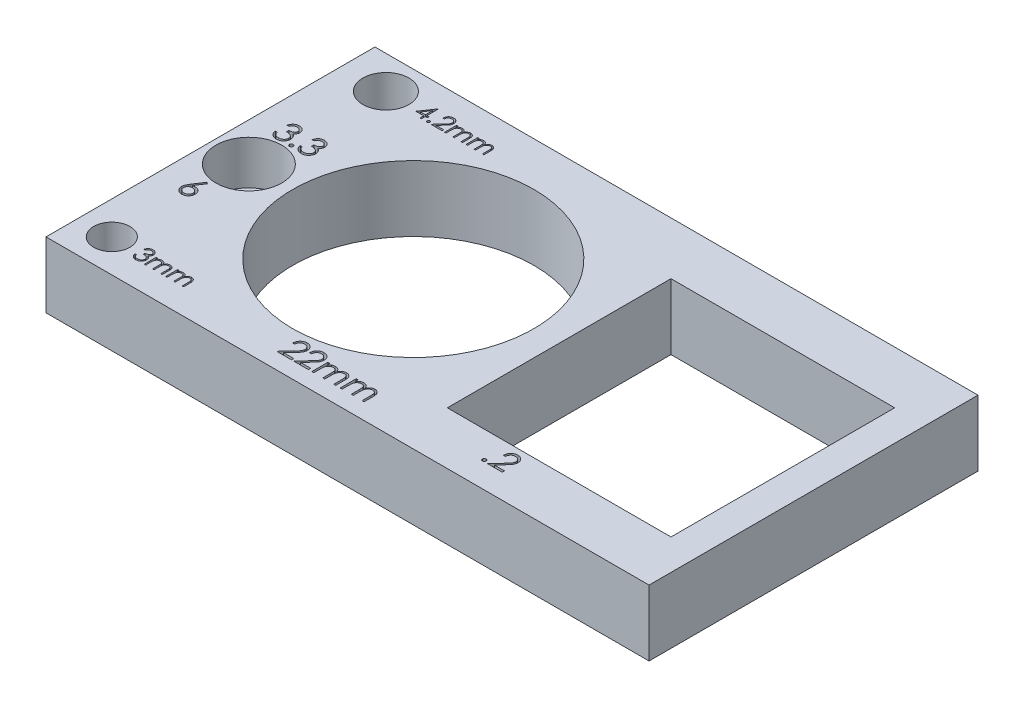
SolidWorks part; units mm, degrees
ref_plane "Front Plane" through (0, 0, 0) normal (0, 0, 1) x (1, 0, 0)
ref_plane "Top Plane" through (0, 0, 0) normal (0, 1, 0) x (1, 0, 0)
ref_plane "Right Plane" through (0, 0, 0) normal (1, 0, 0) x (0, 0, -1)
sketch "Sketch1" plane through (0, 0, 0) normal (0, 1, 0) x (1, 0, 0)
  line L1 (-27.5, -15) -> (27.5, -15)
  line L2 (-27.5, -15) -> (-27.5, 15)
  line L3 (-27.5, 15) -> (27.5, 15)
  line L4 (27.5, -15) -> (27.5, 15)
  line L5 (-27.5, -15) -> (27.5, 15) construction
  line L6 (-27.5, 15) -> (27.5, -15) construction
  point P0 (0, 0)
  dimension "D1" = 55
  dimension "D2" = 30
extrude "Boss-Extrude1" add sketch "Sketch1" along normal blind 6
sketch "Sketch2" plane through (0, 0, 0) normal (0, 1, 0) x (1, 0, 0)
  line L10 (27.5, -15) -> (27.5, 15) construction
  line L11 (24.5, -10) -> (4.5, -10) construction
  line L12 (24.5, -10) -> (24.5, 10) construction
  line L13 (24.5, 10) -> (4.5, 10) construction
  line L14 (4.5, -10) -> (4.5, 10) construction
  line L16 (-27.5, -15) -> (27.5, -15) construction
  line L17 (4.3, -10.2) -> (4.3, 10.2)
  line L18 (24.7, 10.2) -> (4.3, 10.2)
  line L19 (24.7, -10.2) -> (24.7, 10.2)
  line L20 (24.7, -10.2) -> (4.3, -10.2)
  dimension "D1" = 20
  dimension "D2" = 20
  dimension "D3" = 3
  dimension "D4" = 5
  dimension "D5" = 0.2
extrude "Cut-Extrude2" cut sketch "Sketch2" against normal through all and the other way through all
sketch "Sketch4" plane through (0, 0, 0) normal (0, 1, 0) x (1, 0, 0)
  line L0 (27.5, 12) -> (-27.5, 12) construction
  line L1 (27.5, -15) -> (27.5, 15) construction
  line L2 (-27.5, 15) -> (-27.5, -15) construction
  line L3 (27.5, 15) -> (-27.5, 15) construction
  circle A0 centre (-23.5, 12) radius 2.1
  dimension "D2" = 4.2
  dimension "D1" = 3
  dimension "D3" = 4
extrude "Cut-Extrude3" cut sketch "Sketch4" along normal blind 10
sketch "Sketch5" plane through (0, 6, 0) normal (0, 1, 0) x (1, 0, 0)
  line L0 (-27.5, -15) -> (27.5, -15) construction
  line L1 (-27.5, 15) -> (-27.5, -15) construction
  circle A0 centre (-24.5, -12) radius 1.65
  dimension "D1" = 3.3
  dimension "D2" = 3
  dimension "D3" = 3
extrude "Cut-Extrude4" cut sketch "Sketch5" against normal through all
sketch "Sketch6" plane through (0, 6, 0) normal (0, 1, 0) x (1, 0, 0)
  text T0 "4.2mm" font "Century Gothic" height 1.5
extrude "Cut-Extrude5" cut sketch "Sketch6" against normal blind 1
sketch "Sketch7" plane through (0, 6, 0) normal (0, 1, 0) x (1, 0, 0)
  text T0 "3mm" font "Century Gothic" height 1.5
extrude "Cut-Extrude6" cut sketch "Sketch7" against normal blind 1
sketch "Sketch8" plane through (0, 6, 0) normal (0, 1, 0) x (1, 0, 0)
  line L0 (-27.5, 15) -> (-27.5, -15) construction
  circle A0 centre (-24, 0) radius 1.65
  dimension "D1" = 3.3
  dimension "D2" = 3.5
extrude "Cut-Extrude7" cut sketch "Sketch8" against normal through all
sketch "Sketch9" plane through (0, 6, 0) normal (0, 1, 0) x (1, 0, 0)
  circle A0 centre (-24, 0) radius 3
  dimension "D1" = 6
extrude "Cut-Extrude8" cut sketch "Sketch9" against normal blind 4
sketch "Sketch10" plane through (0, 6, 0) normal (0, 1, 0) x (1, 0, 0)
  text T0 "3.3\r\n\r\n6" font "Century Gothic" height 2
extrude "Cut-Extrude9" cut sketch "Sketch10" against normal blind 1
sketch "Sketch11" plane through (0, 6, 0) normal (0, 1, 0) x (1, 0, 0)
  text T0 ".2" font "Century Gothic" height 2
extrude "Cut-Extrude10" cut sketch "Sketch11" against normal blind 1
sketch "Sketch12" plane through (0, 6, 0) normal (0, 1, 0) x (1, 0, 0)
  circle A0 centre (-9, 0) radius 11
  dimension "D1" = 22
  dimension "D2" = 9
extrude "Cut-Extrude11" cut sketch "Sketch12" against normal blind 10
sketch "Sketch13" plane through (0, 6, 0) normal (0, 1, 0) x (1, 0, 0)
  text T0 "22mm" font "Century Gothic" height 2
extrude "Cut-Extrude12" cut sketch "Sketch13" against normal blind 1
